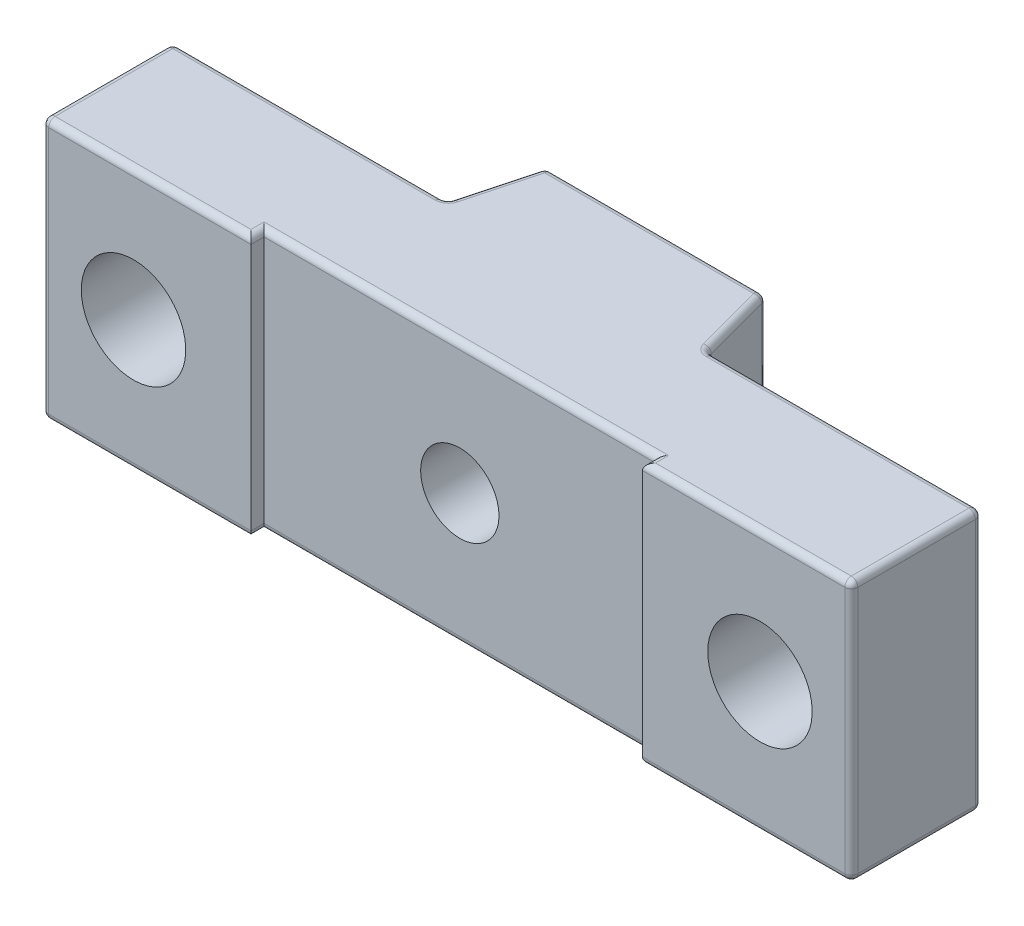
SolidWorks part; units mm, degrees
ref_plane "Front Plane" through (0, 0, 0) normal (0, 0, 1) x (1, 0, 0)
ref_plane "Top Plane" through (0, 0, 0) normal (0, 1, 0) x (1, 0, 0)
ref_plane "Right Plane" through (0, 0, 0) normal (1, 0, 0) x (0, 0, -1)
sketch "Sketch1" plane through (0, 0, 0) normal (0, 1, 0) x (1, 0, 0)
  line L0 (-5, 2.5) -> (-4.1962, 5.5)
  line L1 (15.5, -2.5) -> (-15.5, -2.5)
  line L2 (15.5, -2.5) -> (15.5, 2.5)
  line L3 (15.5, 2.5) -> (5, 2.5)
  line L4 (-15.5, -2.5) -> (-15.5, 2.5)
  line L5 (15.5, -2.5) -> (-15.5, 2.5) construction
  line L6 (15.5, 2.5) -> (-15.5, -2.5) construction
  line L7 (-4.1962, 5.5) -> (4.1962, 5.5)
  line L10 (-5, 2.5) -> (-15.5, 2.5)
  line L11 (0, 5.5) -> (0, 9.9435) construction
  line L12 (5, 2.5) -> (4.1962, 5.5)
  point P0 (0, 0)
  point P8 (0, 0)
  dimension "D1" = 31
  dimension "D2" = 5
  dimension "D3" = 3
  dimension "D5" = 15
extrude "Boss-Extrude1" add sketch "Sketch1" along normal mid plane 10
sketch "Sketch2" plane through (0, 5, 0) normal (0, 1, 0) x (1, 0, 0)
  line L0 (-15.5, -2.5) -> (15.5, -2.5) construction
  line L1 (-7.5, -2.5) -> (7.5, -2.5)
  line L2 (-7.5, -2.5) -> (-7.5, -2)
  line L3 (-7.5, -2) -> (7.5, -2)
  line L4 (7.5, -2.5) -> (7.5, -2)
  point P6 (0, -2)
  dimension "D1" = 7.5
  dimension "D2" = 7.5
  dimension "D3" = 0.5
extrude "Cut-Extrude1" cut sketch "Sketch2" against normal through all
sketch "Sketch3" plane through (0, 0, -2.5) normal (0, 0, -1) x (-1, 0, 0)
  circle A0 centre (0, 0) radius 1.5
  circle A1 centre (12, 0) radius 2
  circle A2 centre (-12, 0) radius 2
  point P7 (0, 0)
  point P8 (0, 0)
  point P9 (0, 0)
  dimension "D1" = 3
  dimension "D2" = 4
  dimension "D3" = 4
  dimension "D4" = 12
  dimension "D5" = 12
extrude "Cut-Extrude2" cut sketch "Sketch3" against normal through all
sketch "Sketch4" plane through (0, 0, -5.5) normal (0, 0, -1) x (-1, 0, 0)
  circle A0 centre (0, 0) radius 1.5
  dimension "D1" = 3
extrude "Cut-Extrude3" cut sketch "Sketch4" against normal through all
fillet "Fillet1" radius 0.25 32 edges at (5, 0, -2.5) (4.1962, 0, -5.5) (-4.1962, 0, -5.5) (-5, 0, -2.5) (-15.5, 0, -2.5) (-15.5, 0, 2.5) (15.5, 0, 2.5) (15.5, 0, -2.5) (0, -5, 2) (7.5, -5, 2.25) (11.5, -5, 2.5) (15.5, -5, 0) (10.25, -5, -2.5) (4.5981, -5, -4) (0, -5, -5.5) (-4.5981, -5, -4) (-10.25, -5, -2.5) (-15.5, -5, 0) (-11.5, -5, 2.5) (-7.5, -5, 2.25) (-15.5, 5, 0) (-10.25, 5, -2.5) (-4.5981, 5, -4) (0, 5, -5.5) (4.5981, 5, -4) (10.25, 5, -2.5) (15.5, 5, 0) (11.5, 5, 2.5) (7.5, 5, 2.25) (0, 5, 2) (-7.5, 5, 2.25) (-11.5, 5, 2.5)
